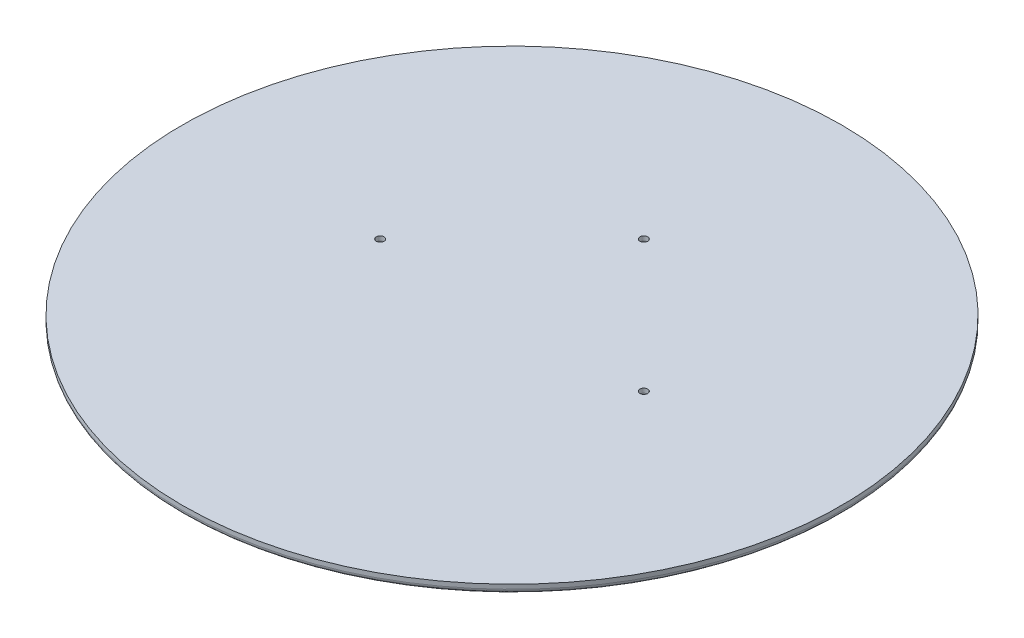
SolidWorks part; units mm, degrees
ref_plane "Front Plane" through (0, 0, 0) normal (0, 0, 1) x (1, 0, 0)
ref_plane "Top Plane" through (0, 0, 0) normal (0, 1, 0) x (1, 0, 0)
ref_plane "Right Plane" through (0, 0, 0) normal (1, 0, 0) x (0, 0, -1)
sketch "Sketch1" plane through (0, 0, 0) normal (0, 1, 0) x (1, 0, 0)
  line L0 (-300, 0) -> (300, 0)
  line L1 (0, 0) -> (0, 300)
  circle A0 centre (0, 0) radius 300
  circle A1 centre (0, 0) radius 750
  circle A2 centre (0, 300) radius 8.89
  circle A3 centre (-300, 0) radius 8.89
  circle A4 centre (300, 0) radius 8.89
extrude "Boss-Extrude1" add sketch "Sketch1" along normal blind 20 contours A1 A4 A0 A3 A2 | A4 L0 A3 A0 | A3 L0 L1 A2 A0 | A4 A0 A2 L1 L0
fillet "Fillet1" radius 10 4 edges at (0, 0, 750) (-300, 0, 8.89) (300, 0, 8.89) (0, 0, -291.11)
sketch "Sketch3" plane through (0, 20, 0) normal (0, 1, 0) x (1, 0, 0)
  line L0 (-473.3865, -333.5264) -> (537.3818, -364.167) construction
  line L1 (0, 0) -> (-325, 0)
  line L2 (0, 0) -> (325, 0)
  line L3 (0, 0) -> (0, 325)
  circle A0 centre (-325, 0) radius 5
  circle A1 centre (325, 0) radius 5
  circle A2 centre (0, 325) radius 5
  text T0 "TOP PLATE" font "Century Gothic" height 100
extrude "Boss-Extrude2" add sketch "Sketch3" against normal blind 47 contours A2 | A0 | A1
sketch "Sketch4" plane through (0, 20, 0) normal (0, 1, 0) x (1, 0, 0)
  line L0 (-472.1741, -300.7798) -> (494.7906, -243.5555)
  text T0 "TOP PLATE" font "Century Gothic" height 100
